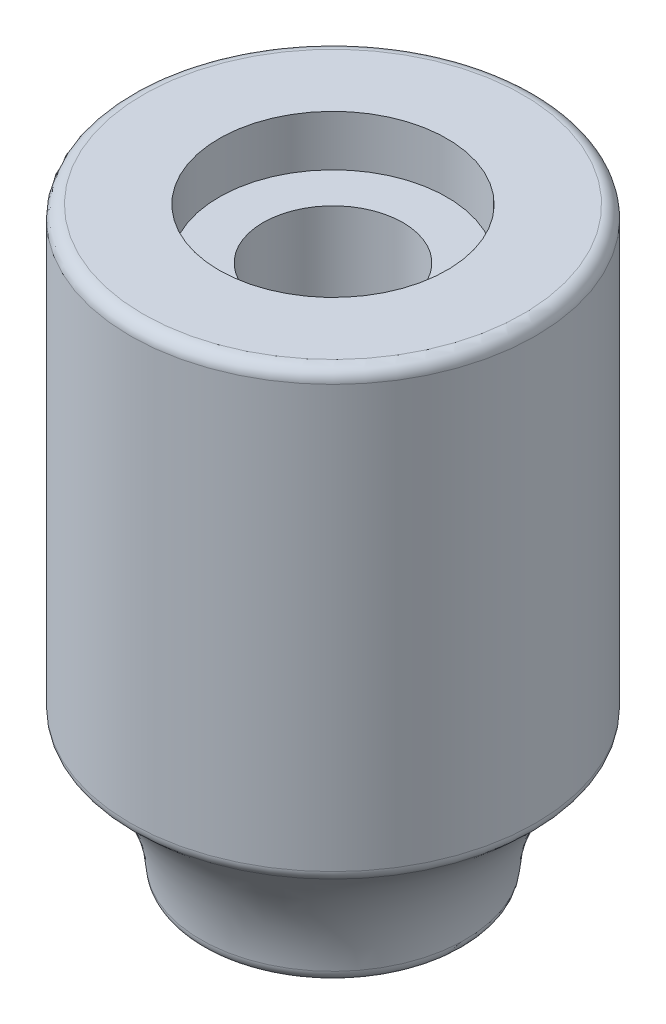
SolidWorks part; units mm, degrees
material "PET"
ref_plane "Front Plane" through (0, 0, 0) normal (0, 0, 1) x (1, 0, 0)
ref_plane "Top Plane" through (0, 0, 0) normal (0, 1, 0) x (1, 0, 0)
ref_plane "Right Plane" through (0, 0, 0) normal (1, 0, 0) x (0, 0, -1)
sketch "Sketch1" plane through (0, 0, 0) normal (0, 1, 0) x (1, 0, 0)
  circle A4 centre (0, 0) radius 25.4
  dimension "D1" = 50.8
extrude "Boss-Extrude1" add sketch "Sketch1" along normal blind 73.025 contours A4
sketch "Sketch2" plane through (0, 73.025, 0) normal (0, 1, 0) x (1, 0, 0)
  circle A0 centre (0, 0) radius 14.2875
  dimension "D1" = 28.575
extrude "Cut-Extrude1" cut sketch "Sketch2" against normal blind 6.35
sketch "Sketch3" plane through (0, 0, 0) normal (0, -1, 0) x (1, 0, 0)
  circle A0 centre (0, 0) radius 14.2875
  dimension "D1" = 28.575
extrude "Cut-Extrude2" cut sketch "Sketch3" against normal blind 6.35
sketch "Sketch4" plane through (0, 6.35, 0) normal (0, -1, 0) x (1, 0, 0)
  circle A0 centre (0, 0) radius 8.763
  dimension "D1" = 17.526
extrude "Cut-Extrude3" cut sketch "Sketch4" against normal through all and the other way through all
sketch "Sketch5" plane through (0, 0, 0) normal (0, -1, 0) x (-1, 0, 0)
  circle A0 centre (0, 0) radius 16.51
  circle A1 centre (0, 0) radius 14.2875 construction
  circle A2 centre (0, 0) radius 25.4
  circle A3 centre (0, 0) radius 25.4 construction
  dimension "D1" = 2.2225
extrude "Cut-Extrude5" cut sketch "Sketch5" against normal blind 17.78
sketch "Sketch10" plane through (0, 0, 0) normal (0, 0, 1) x (1, 0, 0)
  line L0 (-25.4, 17.78) -> (-16.51, 17.78)
  line L1 (-16.51, 17.78) -> (-16.51, 0)
  line L2 (0, 0) -> (0, -14.8609) construction
  arc A2 (-25.4, 17.78) -> (-16.51, 0) centre (-38.735, 0) cw
  point P12 (-20.6627, 5.7337)
  point P13 (0, 0)
revolve "Revolve3" add sketch "Sketch10" angle 360 about L2
fillet "Fillet8" radius 1.5875 3 edges at (0, 73.025, 25.4) (0, 17.78, -25.4) (0, 0, 16.51)
